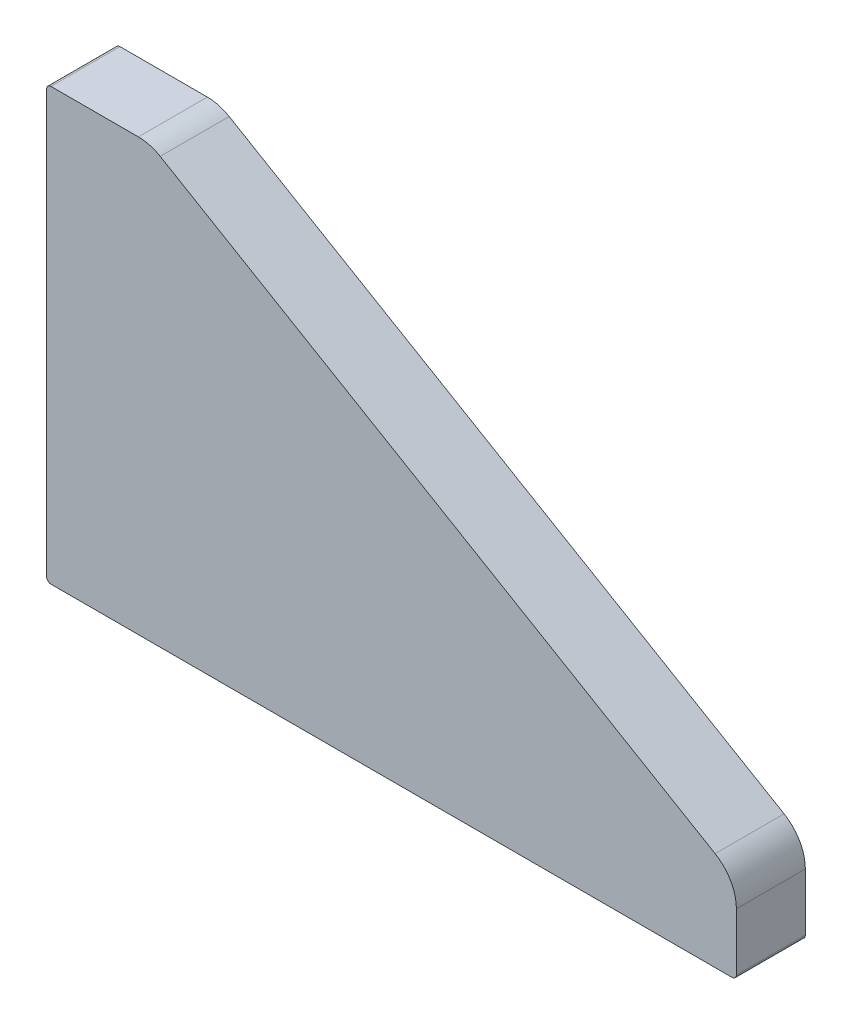
SolidWorks part; units mm, degrees
material "6061-T6 (SS)"
ref_plane "Front Plane" through (0, 0, 0) normal (0, 0, 1) x (1, 0, 0)
ref_plane "Top Plane" through (0, 0, 0) normal (0, 1, 0) x (1, 0, 0)
ref_plane "Right Plane" through (0, 0, 0) normal (1, 0, 0) x (0, 0, -1)
sketch "Sketch1" plane through (0, 0, 0) normal (0, 0, 1) x (1, 0, 0)
  line L0 (0, 0) -> (80, 0)
  line L1 (80, 0) -> (80, 10)
  line L2 (80, 10) -> (12, 50)
  line L3 (12, 50) -> (0, 50)
  line L4 (0, 50) -> (0, 0)
  dimension "D1" = 50
  dimension "D2" = 80
  dimension "D3" = 10
  dimension "D4" = 12
extrude "Boss-Extrude1" add sketch "Sketch1" along normal blind 8
fillet "Fillet1" radius 5 2 edges at (80, 10, 4) (12, 50, 4)
fillet "Fillet3" radius 0.5 3 edges at (0, 0, 4) (0, 50, 4) (80, 0, 4)
hole_wizard "M4 Tapped Hole1" positions "Sketch2" profile "Sketch3" tap size "M4" standard "ISO"
sketch "Sketch2" plane through (0, 0, 0) normal (-1, 0, 0) x (0, 0, 1)
  line L8 (0, 49.5) -> (0, 0.5)
  line L9 (0, 0.5) -> (8, 0.5)
  line L10 (8, 0.5) -> (8, 49.5)
  line L11 (8, 49.5) -> (0, 49.5)
  line L12 (0, 49.5) -> (0, 0.5) construction
  line L14 (8, 0.5) -> (8, 49.5) construction
  line L15 (8, 49.5) -> (0, 49.5) construction
  line L16 (8, 0) -> (8, 0.5) construction
  line L17 (8, 0) -> (0, 0) construction
  line L18 (0, 0.5) -> (0, 0) construction
  line L19 (8, 0) -> (8, 0.5) construction
  line L20 (8, 0) -> (0, 0) construction
  line L21 (0, 0.5) -> (0, 0) construction
  point P0 (4, 43.5)
  point P2 (4, 6)
  point P56 (4, 0)
  dimension "D2" = 6
  dimension "D3" = 6
  dimension "D1" = 0
sketch "Sketch3" plane through (0, 43.5, 4) normal (0, 1, 0) x (0, 0, 1)
  line L0 (0, 0) -> (0, 15.5914)
  line L1 (0, 15.5914) -> (1.65, 14.6)
  line L2 (1.65, 14.6) -> (1.65, 0)
  line L5 (1.65, 0) -> (0, 0)
  line L10 (0, 15.5914) -> (-1.65, 14.6) construction
  line L11 (0, -6.35) -> (0, 107.95) construction
  dimension "Tap Drill Dia." = 3.3
  dimension "Tap Drill Depth" = 14.6
  dimension "Drill Angle" = 118
cosmetic thread "Hole Thread1" parameters "D1"=12.5, "D2"=4
cosmetic thread "Hole Thread2" parameters "D1"=12.5, "D2"=4
hole_wizard "M4 Tapped Hole2" positions "Sketch4" profile "Sketch5" tap size "M4" standard "ISO"
sketch "Sketch4" plane through (0, 0, 0) normal (0, -1, 0) x (-1, 0, 0)
  line L1 (-80, -4) -> (0, -4)
  line L2 (-80, -8) -> (-80, 0) construction
  line L3 (0, 0) -> (0, -8) construction
  point P0 (-20, -4)
  point P2 (-65, -4)
  dimension "D1" = 20
  dimension "D2" = 15
sketch "Sketch5" plane through (20, 0, 4) normal (1, 0, 0) x (0, 0, -1)
  line L0 (0, 0) -> (0, 15.5914)
  line L1 (0, 15.5914) -> (1.65, 14.6)
  line L2 (1.65, 14.6) -> (1.65, 0)
  line L5 (1.65, 0) -> (0, 0)
  line L10 (0, 15.5914) -> (-1.65, 14.6) construction
  line L11 (0, -6.35) -> (0, 107.95) construction
  dimension "Tap Drill Dia." = 3.3
  dimension "Tap Drill Depth" = 14.6
  dimension "Drill Angle" = 118
cosmetic thread "Hole Thread3" parameters "D1"=12.5, "D2"=4
cosmetic thread "Hole Thread4" parameters "D1"=12.5, "D2"=4
